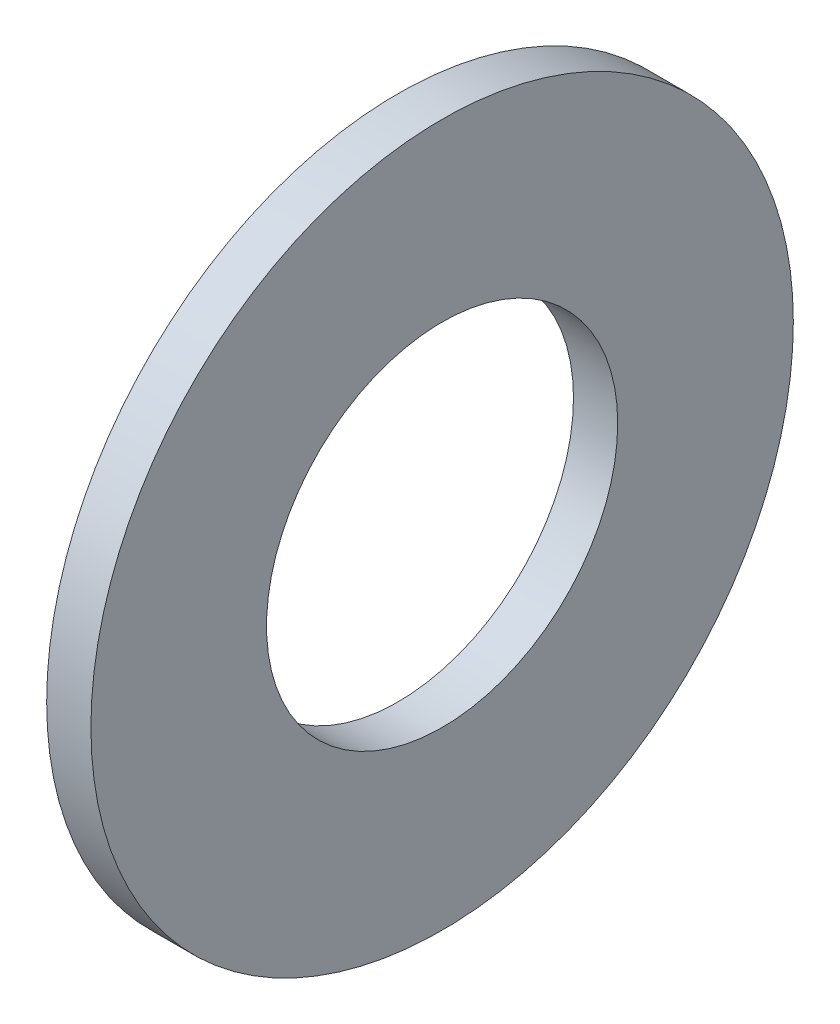
SolidWorks part; units mm, degrees
ref_plane "Front" through (0, 0, 0) normal (0, 0, 1) x (1, 0, 0)
ref_plane "Top" through (0, 0, 0) normal (0, 1, 0) x (1, 0, 0)
ref_plane "Right" through (0, 0, 0) normal (1, 0, 0) x (0, 0, -1)
sketch "Sketch1" plane through (0, 0, 0) normal (1, 0, 0) x (0, 0, -1)
  circle A0 centre (0, 0) radius 3.175
  circle A1 centre (0, 0) radius 6.35
  dimension "D1" = 6.35
  dimension "D2" = 12.7
extrude "Boss-Extrude1" add sketch "Sketch1" along normal blind 0.8
